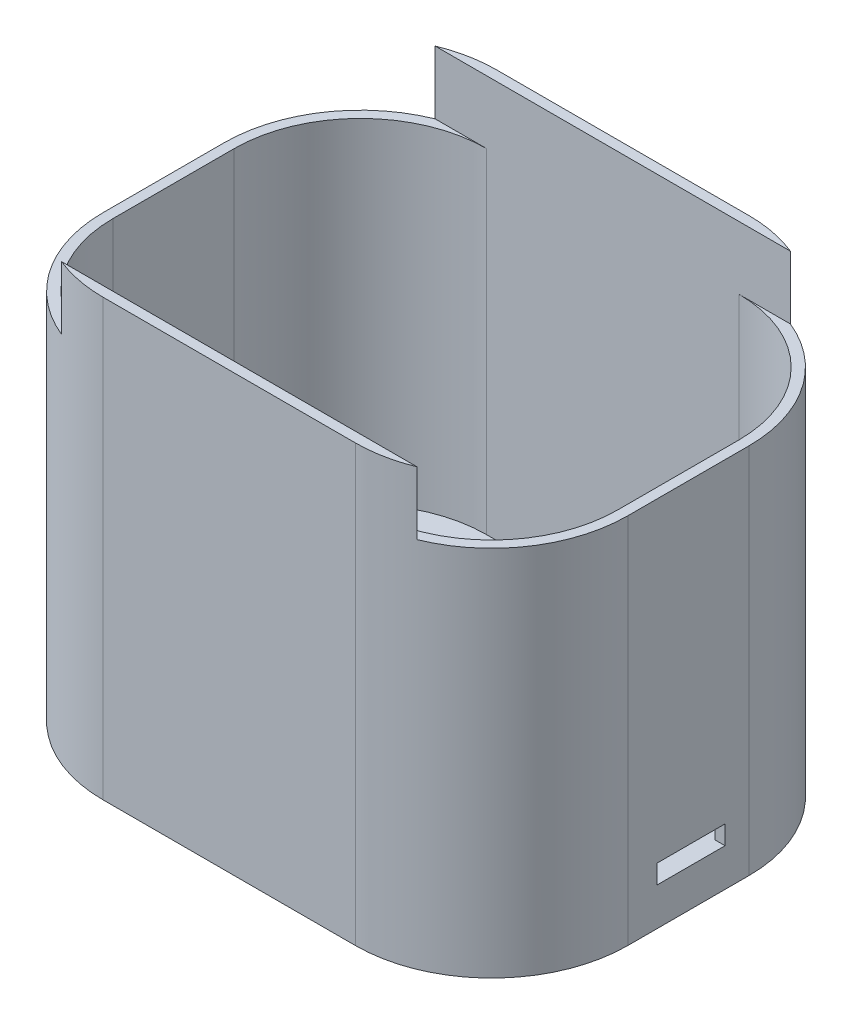
SolidWorks part; units mm, degrees
ref_plane "前基準面" through (0, 0, 0) normal (0, 0, 1) x (1, 0, 0)
ref_plane "上基準面" through (0, 0, 0) normal (0, 1, 0) x (1, 0, 0)
ref_plane "右基準面" through (0, 0, 0) normal (1, 0, 0) x (0, 0, -1)
sketch "草圖1" plane through (0, 0, 0) normal (0, 1, 0) x (1, 0, 0)
  line L0 (-10, -15.6) -> (10, -15.6)
  line L1 (-10, -14.8) -> (10, -14.8)
  line L2 (-20, -4.8) -> (-20, 4.8)
  line L3 (-10, 14.8) -> (10, 14.8)
  line L4 (20, -4.8) -> (20, 4.8)
  line L5 (-20, -14.8) -> (20, 14.8) construction
  line L6 (-20, 14.8) -> (20, -14.8) construction
  line L7 (20.8, -4.8) -> (20.8, 4.8)
  line L8 (-10, 15.6) -> (10, 15.6)
  line L9 (-20.8, -4.8) -> (-20.8, 4.8)
  arc A0 (-20, 4.8) -> (-10, 14.8) centre (-10, 4.8) cw
  arc A1 (10, 14.8) -> (20, 4.8) centre (10, 4.8) cw
  arc A2 (20, -4.8) -> (10, -14.8) centre (10, -4.8) cw
  arc A3 (-10, -14.8) -> (-20, -4.8) centre (-10, -4.8) cw
  arc A4 (20.8, -4.8) -> (10, -15.6) centre (10, -4.8) cw
  arc A5 (10, 15.6) -> (20.8, 4.8) centre (10, 4.8) cw
  arc A6 (-20.8, 4.8) -> (-10, 15.6) centre (-10, 4.8) cw
  arc A7 (-10, -15.6) -> (-20.8, -4.8) centre (-10, -4.8) cw
  point P0 (0, 0)
  dimension "D3" = 10
  dimension "D4" = 10
  dimension "D1" = 40
  dimension "D2" = 29.6
  dimension "D5" = 0.8
extrude "填料-伸長1" add sketch "草圖1" along normal blind 34.5
sketch "草圖4" plane through (0, 34.5, 0) normal (0, 1, 0) x (1, 0, 0)
  line L0 (10, 14.8) -> (-10, 14.8) construction
  line L1 (-20.8, -14.8) -> (20.8, -14.8)
  line L2 (-20.8, -14.8) -> (-20.8, 14.8)
  line L3 (-20.8, 14.8) -> (20.8, 14.8)
  line L4 (20.8, -14.8) -> (20.8, 14.8)
  line L5 (-20.8, -14.8) -> (20.8, 14.8) construction
  line L6 (-20.8, 14.8) -> (20.8, -14.8) construction
  line L8 (-20.8, 4.8) -> (-20.8, -4.8) construction
  point P0 (0, 0)
  point P8 (-20.8, 0)
extrude "除料-伸長1" cut sketch "草圖4" against normal blind 5
sketch "草圖5" plane through (0, 0, 0) normal (0, -1, 0) x (1, 0, 0)
  line L0 (20, 4.8) -> (20, -4.8) construction
  line L1 (-10, 14.8) -> (10, 14.8) construction
  line L2 (10, -14.8) -> (-10, -14.8) construction
  line L3 (-20, -4.8) -> (-20, 4.8) construction
  line L4 (20, 4.8) -> (20, -4.8)
  line L5 (-10, 14.8) -> (10, 14.8)
  line L6 (10, -14.8) -> (-10, -14.8)
  line L7 (-20, -4.8) -> (-20, 4.8)
  arc A0 (20, 4.8) -> (10, 14.8) centre (10, 4.8) ccw construction
  arc A1 (10, -14.8) -> (20, -4.8) centre (10, -4.8) ccw construction
  arc A2 (-20, -4.8) -> (-10, -14.8) centre (-10, -4.8) ccw construction
  arc A3 (-10, 14.8) -> (-20, 4.8) centre (-10, 4.8) ccw construction
  arc A4 (20, 4.8) -> (10, 14.8) centre (10, 4.8) ccw
  arc A5 (10, -14.8) -> (20, -4.8) centre (10, -4.8) ccw
  arc A6 (-20, -4.8) -> (-10, -14.8) centre (-10, -4.8) ccw
  arc A7 (-10, 14.8) -> (-20, 4.8) centre (-10, 4.8) ccw
extrude "填料-伸長2" add sketch "草圖5" against normal blind 3
sketch "草圖6" plane through (20.8, 0, 0) normal (1, 0, 0) x (0, 0, -1)
  line L3 (-2.5, 3) -> (2.9, 3)
  line L6 (-2.5, 3) -> (-2.5, 4.5)
  line L7 (-2.5, 4.5) -> (2.9, 4.5)
  line L8 (2.9, 4.5) -> (2.9, 3)
  line L9 (-4.8, 29.5) -> (4.8, 29.5) construction
  dimension "D1" = 5.4
  dimension "D2" = 1.5
  dimension "D3" = 25
extrude "除料-伸長2" cut sketch "草圖6" against normal through all
sketch "草圖7" plane through (0, 0, 0) normal (0, -1, 0) x (1, 0, 0)
  circle A0 centre (0, 0) radius 1.22
  circle A1 centre (4, 0) radius 0.91
  circle A2 centre (8, 0) radius 1.3
  circle A3 centre (-4, 0) radius 0.91
  circle A4 centre (-8, 0) radius 1.68
  circle A5 centre (-12, 0) radius 0.95
  circle A6 centre (12, 0) radius 0.85
  dimension "D1" = 4
  dimension "D5" = 3.36
  dimension "D6" = 2.6
  dimension "D7" = 1.82
  dimension "D8" = 1.82
  dimension "D9" = 2.44
  dimension "D10" = 4
  dimension "D12" = 1.9
  dimension "D13" = 1.7
  dimension "D2" = 4
  dimension "D3" = 4
  dimension "D4" = 4
  dimension "D11" = 4
extrude "除料-伸長3" cut sketch "草圖7" against normal through all
